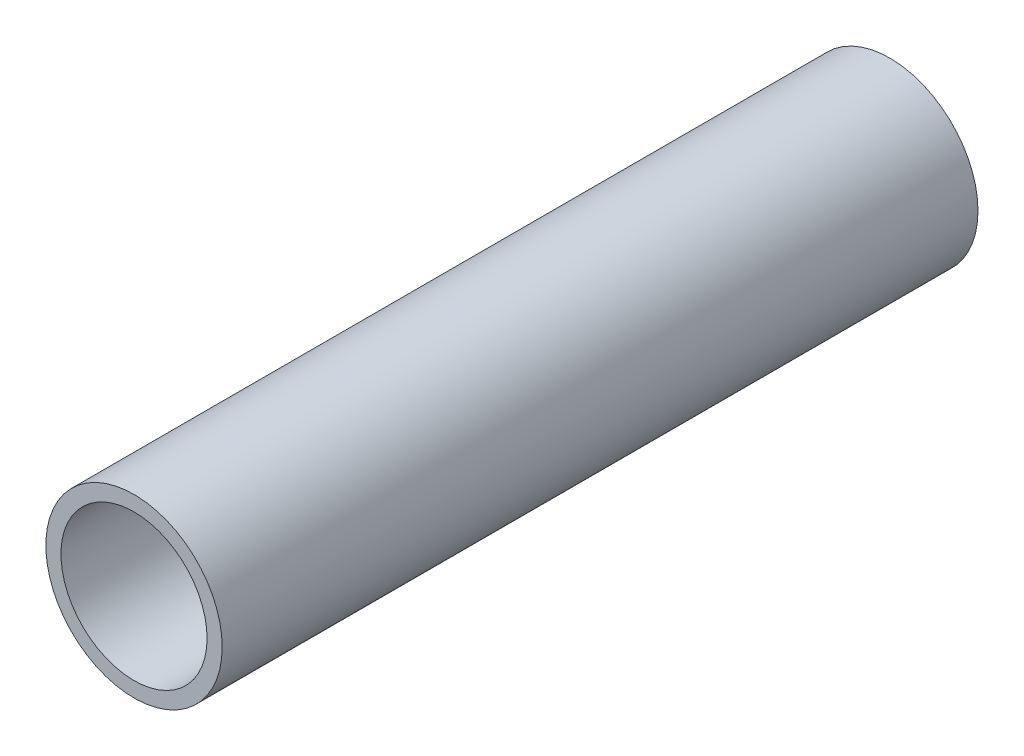
SolidWorks part; units mm, degrees
ref_plane "前视基准面" through (0, 0, 0) normal (0, 0, 1) x (1, 0, 0)
ref_plane "上视基准面" through (0, 0, 0) normal (0, 1, 0) x (1, 0, 0)
ref_plane "右视基准面" through (0, 0, 0) normal (1, 0, 0) x (0, 0, -1)
sketch "草图1" plane through (0, 0, 0) normal (0, 0, 1) x (1, 0, 0)
  circle A0 centre (0, 0) radius 1.75
  circle A1 centre (0, 0) radius 1.45
  dimension "D1" = 3.5
  dimension "D2" = 0.3
extrude "凸台-拉伸1" add sketch "草图1" along normal blind 15
